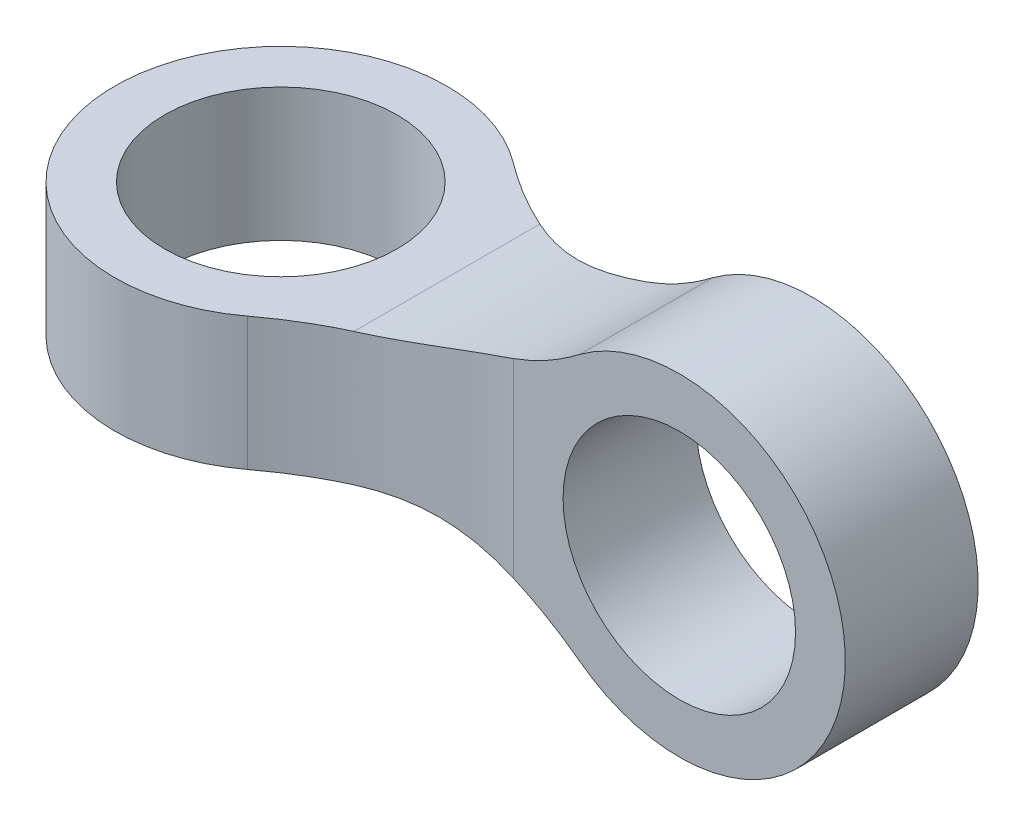
SolidWorks part; units mm, degrees
ref_plane "Front Plane" through (0, 0, 0) normal (0, 0, 1) x (1, 0, 0)
ref_plane "Top Plane" through (0, 0, 0) normal (0, 1, 0) x (1, 0, 0)
ref_plane "Right Plane" through (0, 0, 0) normal (1, 0, 0) x (0, 0, -1)
sketch "Sketch1" plane through (0, 0, 0) normal (0, 1, 0) x (1, 0, 0)
  line L3 (0, 0) -> (120, 0) construction
  line L8 (90, 20) -> (190, 20)
  line L9 (190, 20) -> (190, -20)
  line L10 (190, -20) -> (90, -20)
  circle A0 centre (0, 0) radius 35
  arc A1 (30, 40) -> (30, -40) centre (0, 0) ccw
  spline S0 degree 3 poles (30, 40) (53.5221, 22.3584) (73.7408, 19.9573) (90, 20) knots 0 0 0 0 0.5 0.5 0.5 0.5
  spline S1 degree 3 poles (30, -40) (53.5221, -22.3584) (73.7408, -19.9573) (90, -20) knots 0 0 0 0 0.5 0.5 0.5 0.5
  point P5 (0, 0)
  point P7 (9.0275, 47.8366)
  point P9 (190, 0)
  point P11 (0, 0)
  point P14 (0, 0)
  point P15 (10.3917, -49.1783)
  point P16 (0, 0)
  point P17 (0, 0)
  point P18 (0, 0)
  dimension "D1" = 70
  dimension "D2" = 100
  dimension "D3" = 80
  dimension "D4" = 60
  dimension "D5" = 100
  dimension "D6" = 40
extrude "Boss-Extrude1" add sketch "Sketch1" along normal mid plane 120
sketch "Sketch3" plane through (0, 0, -20) normal (0, 0, -1) x (-1, 0, 0)
  line L0 (-190, 60) -> (-190, -60) construction
  line L1 (-50, -20) -> (50, -20)
  line L2 (50, -20) -> (50, 20)
  line L3 (50, 20) -> (-50, 20)
  line L4 (50, -60) -> (50, 60) construction
  circle A0 centre (-140, 0) radius 35
  arc A1 (-110, 40) -> (-110, -40) centre (-140, 0) ccw
  spline S0 degree 3 poles (-110, 40) (-99.4967, 32.1225) (-87.3896, 27.686) (-61.5065, 20) (-50, 20) knots 0 0 0 0 0.549429 1 1 1 1
  spline S1 degree 3 poles (-110, -40) (-100.0934, -32.57) (-80.6592, -23.1393) (-60.9321, -20) (-50, -20) knots 0 0 0 0 0.546701 1 1 1 1
  point P11 (50, 0)
  point P16 (0, 0)
  point P17 (0, 0)
  point P18 (-82.0341, 26.2665)
  point P19 (-78.7564, -24.1389)
  dimension "D1" = 100
  dimension "D2" = 70
  dimension "D5" = 80
  dimension "D3" = 100
  dimension "D4" = 40
extrude "Cut-Extrude2" cut sketch "Sketch3" against normal through all both and the other way through all flip side to cut
